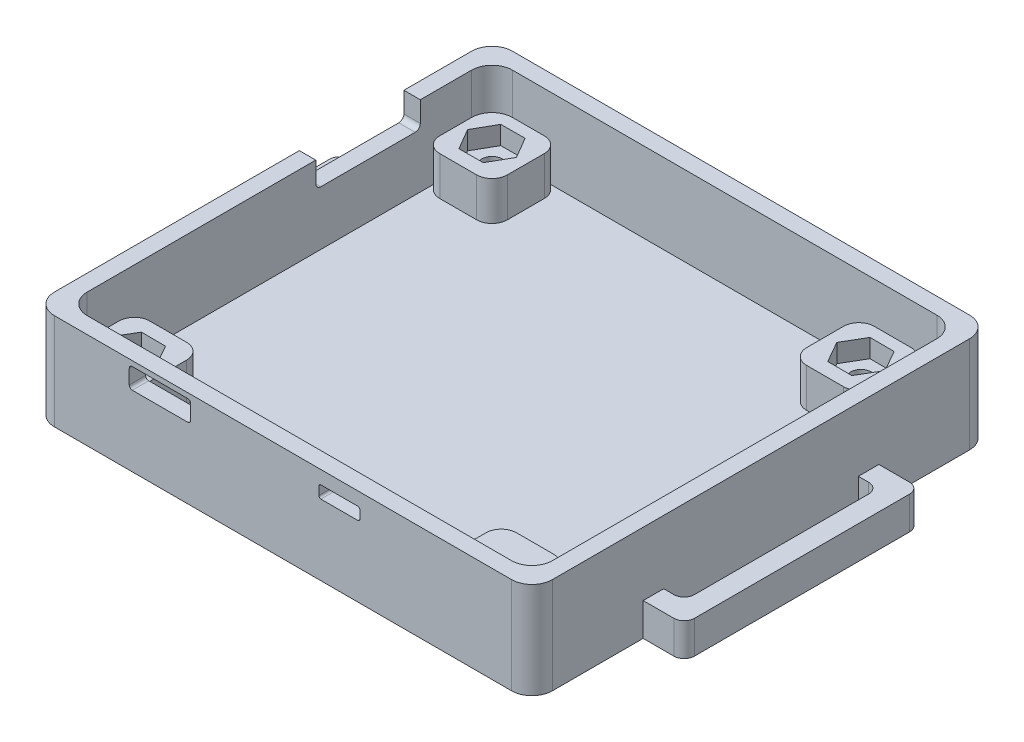
SolidWorks part; units mm, degrees
ref_plane "前视基准面" through (0, 0, 0) normal (0, 0, 1) x (1, 0, 0)
ref_plane "上视基准面" through (0, 0, 0) normal (0, 1, 0) x (1, 0, 0)
ref_plane "右视基准面" through (0, 0, 0) normal (1, 0, 0) x (0, 0, -1)
other "Configuration Table"
sketch "草图1" plane through (0, 0, 0) normal (0, 1, 0) x (1, 0, 0)
  line L0 (-22.3, 20.35) -> (22.3, -20.35) construction
  line L1 (-22.3, -22.35) -> (22.3, -22.35)
  line L2 (-24.3, -20.35) -> (-24.3, 20.35)
  line L3 (-22.3, 22.35) -> (22.3, 22.35)
  line L4 (24.3, -20.35) -> (24.3, 20.35)
  line L5 (0, 22.35) -> (0, -22.35) construction
  line L6 (-14.7715, 0) -> (34.2942, 0) construction
  line L7 (22.3, 20.35) -> (-22.3, -20.35) construction
  arc A0 (-22.3, -22.35) -> (-24.3, -20.35) centre (-22.3, -20.35) cw
  arc A1 (22.3, -22.35) -> (24.3, -20.35) centre (22.3, -20.35) ccw
  arc A2 (22.3, 22.35) -> (24.3, 20.35) centre (22.3, 20.35) cw
  arc A3 (-24.3, 20.35) -> (-22.3, 22.35) centre (-22.3, 20.35) cw
  point P0 (0, 0)
  point P6 (-24.3, -22.35)
  point P9 (24.3, -22.35)
  point P15 (-24.3, 22.35)
  point P16 (0, 0)
  point P17 (0, 0)
  dimension "D3" = 2
  dimension "D1" = 44.7
  dimension "D2" = 48.6
extrude "凸台-拉伸1" add sketch "草图1" along normal blind 9.4
sketch "草图2" plane through (0, 9.4, 0) normal (0, 1, 0) x (1, 0, 0)
  line L1 (-20.7, -20.75) -> (20.7, -20.75)
  line L2 (-22.7, -18.75) -> (-22.7, 18.75)
  line L3 (-20.7, 20.75) -> (20.7, 20.75)
  line L4 (22.7, -18.75) -> (22.7, 18.75)
  line L5 (0, 20.75) -> (0, -20.75) construction
  line L6 (-22.7, 0) -> (22.7, 0) construction
  arc A0 (20.7, -20.75) -> (22.7, -18.75) centre (20.7, -18.75) ccw
  arc A1 (-20.7, -20.75) -> (-22.7, -18.75) centre (-20.7, -18.75) cw
  arc A2 (20.7, 20.75) -> (22.7, 18.75) centre (20.7, 18.75) cw
  arc A3 (-22.7, 18.75) -> (-20.7, 20.75) centre (-20.7, 18.75) cw
  point P0 (0, 0)
  point P9 (-22.7, -20.75)
  point P12 (22.7, 20.75)
  point P15 (-22.7, 20.75)
  dimension "D3" = 2
  dimension "D1" = 41.5
  dimension "D2" = 45.4
extrude "切除-拉伸1" cut sketch "草图2" against normal blind 7.8
sketch "草图3" plane through (0, 1.6, 0) normal (0, 1, 0) x (1, 0, 0)
  line L0 (-22.7, 18.75) -> (-22.7, -18.75) construction
  line L1 (-21.2, -14.15) -> (-17.6, -14.15)
  line L2 (-22.7, -15.65) -> (-22.7, -20.75)
  line L3 (-22.7, -20.75) -> (-17.6, -20.75)
  line L4 (-16.1, -15.65) -> (-16.1, -19.25)
  line L8 (-20.7, -20.75) -> (20.7, -20.75) construction
  line L9 (-20.7, -20.75) -> (20.7, -20.75) construction
  line L10 (0, 0) -> (-37.0152, 0) construction
  line L11 (-22.7, 20.75) -> (-17.6, 20.75)
  line L12 (-16.1, 15.65) -> (-16.1, 19.25)
  line L13 (-21.2, 14.15) -> (-17.6, 14.15)
  line L14 (-22.7, 15.65) -> (-22.7, 20.75)
  line L15 (-1.5, 15.7499) -> (-1.5, -23.3817) construction
  line L16 (19.7, 15.65) -> (19.7, 19.25)
  line L17 (18.2, 20.75) -> (14.6, 20.75)
  line L18 (13.1, 15.65) -> (13.1, 19.25)
  line L19 (18.2, 14.15) -> (14.6, 14.15)
  line L20 (18.2, -14.15) -> (14.6, -14.15)
  line L21 (13.1, -15.65) -> (13.1, -19.25)
  line L22 (18.2, -20.75) -> (14.6, -20.75)
  line L23 (19.7, -15.65) -> (19.7, -19.25)
  arc A0 (-17.6, -20.75) -> (-16.1, -19.25) centre (-17.6, -19.25) ccw
  arc A1 (-21.2, -14.15) -> (-22.7, -15.65) centre (-21.2, -15.65) ccw
  arc A2 (-17.6, -14.15) -> (-16.1, -15.65) centre (-17.6, -15.65) cw
  arc A3 (-17.6, 20.75) -> (-16.1, 19.25) centre (-17.6, 19.25) cw
  arc A4 (-17.6, 14.15) -> (-16.1, 15.65) centre (-17.6, 15.65) ccw
  arc A5 (-21.2, 14.15) -> (-22.7, 15.65) centre (-21.2, 15.65) cw
  arc A6 (18.2, 14.15) -> (19.7, 15.65) centre (18.2, 15.65) ccw
  arc A7 (14.6, 20.75) -> (13.1, 19.25) centre (14.6, 19.25) ccw
  arc A8 (14.6, 14.15) -> (13.1, 15.65) centre (14.6, 15.65) cw
  arc A9 (19.7, 19.25) -> (18.2, 20.75) centre (18.2, 19.25) ccw
  arc A10 (18.2, -14.15) -> (19.7, -15.65) centre (18.2, -15.65) cw
  arc A11 (14.6, -14.15) -> (13.1, -15.65) centre (14.6, -15.65) ccw
  arc A12 (14.6, -20.75) -> (13.1, -19.25) centre (14.6, -19.25) cw
  arc A13 (19.7, -19.25) -> (18.2, -20.75) centre (18.2, -19.25) cw
  point P13 (-16.1, -20.75)
  point P16 (-22.7, -14.15)
  point P19 (-16.1, -14.15)
  point P47 (19.7, 20.75)
  dimension "D3" = 1.5
  dimension "D5" = 1.5
  dimension "D1" = 6.6
  dimension "D2" = 6.6
  dimension "D4" = 21.2
extrude "凸台-拉伸2" add sketch "草图3" along normal blind 3.8
sketch "草图4" plane through (0, 5.4, 0) normal (0, 1, 0) x (1, 0, 0)
  line L0 (-22.7, 18.75) -> (-22.7, -18.75) construction
  line L1 (-18.329, -19.6072) -> (-17.1329, -17.5645)
  line L2 (-17.1329, -17.5645) -> (-18.3039, -15.5073)
  line L3 (-18.3039, -15.5073) -> (-20.671, -15.4928)
  line L4 (-20.671, -15.4928) -> (-21.8671, -17.5355)
  line L5 (-21.8671, -17.5355) -> (-20.6961, -19.5927)
  line L6 (-20.6961, -19.5927) -> (-18.329, -19.6072)
  line L8 (-20.7, -20.75) -> (20.7, -20.75) construction
  line L9 (0, 0) -> (-33.3871, 0) construction
  line L10 (-20.6961, 19.5927) -> (-18.329, 19.6072)
  line L11 (-21.8671, 17.5355) -> (-20.6961, 19.5927)
  line L12 (-20.671, 15.4928) -> (-21.8671, 17.5355)
  line L13 (-18.3039, 15.5073) -> (-20.671, 15.4928)
  line L14 (-17.1329, 17.5645) -> (-18.3039, 15.5073)
  line L15 (-18.329, 19.6072) -> (-17.1329, 17.5645)
  line L16 (-1.5, 15.3612) -> (-1.5, -12.6702) construction
  line L17 (18.8671, 17.5355) -> (17.6961, 19.5927)
  line L18 (17.671, 15.4928) -> (18.8671, 17.5355)
  line L19 (15.3039, 15.5073) -> (17.671, 15.4928)
  line L20 (14.1329, 17.5645) -> (15.3039, 15.5073)
  line L21 (15.329, 19.6072) -> (14.1329, 17.5645)
  line L22 (17.6961, 19.5927) -> (15.329, 19.6072)
  circle A0 centre (-19.5, -17.55) radius 2.05 construction
  dimension "D1" = 4.1
  dimension "D2" = 3.2
  dimension "D3" = 3.2
  dimension "D4" = 21.2
sketch "草图5" plane through (0, 5.4, 0) normal (0, 1, 0) x (1, 0, 0)
  line L0 (-22.7, 18.75) -> (-22.7, -18.75) construction
  line L2 (-20.7, -20.75) -> (20.7, -20.75) construction
  line L3 (0, 0) -> (-40.1682, 0) construction
  line L4 (-1.5, 11.1284) -> (-1.5, -10.2514) construction
  circle A0 centre (-19.5, -17.55) radius 1
  circle A3 centre (-19.5, 17.55) radius 1
  circle A4 centre (16.5, 17.55) radius 1
  dimension "D1" = 3.2
  dimension "D2" = 3.2
  dimension "D3" = 21.2
extrude "切除-拉伸2" cut sketch "草图4" against normal blind 1.8
extrude "切除-拉伸4" cut sketch "草图5" against normal blind 3.8
sketch "草图6" plane through (-24.3, 0, 0) normal (-1, 0, 0) x (0, 0, 1)
  line L1 (-13.25, 6.9) -> (-4.05, 6.9)
  line L2 (-13.75, 7.4) -> (-13.75, 10.4)
  line L3 (-13.75, 10.4) -> (-3.55, 10.4)
  line L4 (-3.55, 7.4) -> (-3.55, 10.4)
  line L5 (-8.65, 10.4) -> (-8.65, 6.9) construction
  line L6 (-13.75, 8.9) -> (-3.55, 8.9) construction
  line L9 (20.75, 5.4) -> (20.75, 9.4) construction
  line L11 (-15.65, 1.6) -> (15.65, 1.6) construction
  arc A0 (-4.05, 6.9) -> (-3.55, 7.4) centre (-4.05, 7.4) ccw
  arc A1 (-13.25, 6.9) -> (-13.75, 7.4) centre (-13.25, 7.4) cw
  point P0 (-8.65, 8.9)
  dimension "D5" = 0.5
  dimension "D1" = 29.4
  dimension "D2" = 10.2
  dimension "D3" = 3.5
  dimension "D4" = 5.3
extrude "切除-拉伸5" cut sketch "草图6" against normal blind 2.8
sketch "草图7" plane through (0, 0, 22.35) normal (0, 0, 1) x (1, 0, 0)
  line L0 (-22.7, 5.4) -> (-22.7, 1.6) construction
  line L1 (-14.7, 8.9) -> (-9.3, 8.9)
  line L2 (-15, 8.6) -> (-15, 7.2)
  line L3 (-14.7, 6.9) -> (-9.3, 6.9)
  line L4 (-9, 8.6) -> (-9, 7.2)
  line L5 (-12, 6.9) -> (-12, 8.9) construction
  line L6 (-15, 7.9) -> (-9, 7.9) construction
  line L7 (-17.6, 1.6) -> (14.6, 1.6) construction
  arc A0 (-15, 7.2) -> (-14.7, 6.9) centre (-14.7, 7.2) ccw
  arc A1 (-9.3, 6.9) -> (-9, 7.2) centre (-9.3, 7.2) ccw
  arc A2 (-9.3, 8.9) -> (-9, 8.6) centre (-9.3, 8.6) cw
  arc A3 (-14.7, 8.9) -> (-15, 8.6) centre (-14.7, 8.6) ccw
  point P0 (-12, 7.9)
  point P10 (-15, 6.9)
  point P13 (-9, 6.9)
  point P16 (-9, 8.9)
  dimension "D5" = 0.3
  dimension "D1" = 10.7
  dimension "D2" = 6
  dimension "D3" = 2
  dimension "D4" = 5.3
extrude "切除-拉伸6" cut sketch "草图7" against normal blind 2.8
sketch "草图8" plane through (0, 0, 22.35) normal (0, 0, 1) x (1, 0, 0)
  line L0 (-22.7, 5.4) -> (-22.7, 1.6) construction
  line L1 (3.7, 8.1) -> (7.3, 8.1)
  line L2 (3.5, 7.9) -> (3.5, 7.1)
  line L3 (3.7, 6.9) -> (7.3, 6.9)
  line L4 (7.5, 7.9) -> (7.5, 7.1)
  line L5 (5.5, 6.9) -> (5.5, 8.1) construction
  line L6 (3.5, 7.5) -> (7.5, 7.5) construction
  line L7 (-17.6, 1.6) -> (14.6, 1.6) construction
  arc A0 (3.5, 7.1) -> (3.7, 6.9) centre (3.7, 7.1) ccw
  arc A1 (7.3, 6.9) -> (7.5, 7.1) centre (7.3, 7.1) ccw
  arc A2 (7.3, 8.1) -> (7.5, 7.9) centre (7.3, 7.9) cw
  arc A3 (3.7, 8.1) -> (3.5, 7.9) centre (3.7, 7.9) ccw
  point P0 (5.5, 7.5)
  point P10 (3.5, 6.9)
  point P13 (7.5, 6.9)
  point P19 (3.5, 8.1)
  dimension "D5" = 0.2
  dimension "D1" = 28.2
  dimension "D2" = 5.3
  dimension "D3" = 4
  dimension "D4" = 1.2
extrude "切除-拉伸7" cut sketch "草图8" against normal blind 2.8
sketch "草图12" plane through (0, 1.6, 0) normal (0, 1, 0) x (1, 0, 0)
  line L0 (-24.3, 20.35) -> (-24.3, -20.35) construction
  line L1 (-27.3, 11.5) -> (-24.3, 11.5)
  line L2 (-28.3, 10.5) -> (-28.3, -10.5)
  line L3 (-27.3, -11.5) -> (-24.3, -11.5)
  line L4 (-24.3, 11.5) -> (-24.3, -11.5)
  line L5 (-25.8, -11.5) -> (-25.8, 11.5) construction
  line L6 (-28.3, 0) -> (-24.3, 0) construction
  line L7 (0, 24.1491) -> (0, -25.1278) construction
  line L8 (22.3, 22.35) -> (-22.3, 22.35) construction
  line L9 (27.3, -11.5) -> (24.3, -11.5)
  line L10 (24.3, 11.5) -> (24.3, -11.5)
  line L11 (27.3, 11.5) -> (24.3, 11.5)
  line L12 (28.3, 10.5) -> (28.3, -10.5)
  arc A0 (-28.3, -10.5) -> (-27.3, -11.5) centre (-27.3, -10.5) ccw
  arc A1 (-27.3, 11.5) -> (-28.3, 10.5) centre (-27.3, 10.5) ccw
  arc A2 (28.3, -10.5) -> (27.3, -11.5) centre (27.3, -10.5) cw
  arc A3 (27.3, 11.5) -> (28.3, 10.5) centre (27.3, 10.5) cw
  point P0 (-25.8, 0)
  dimension "D3" = 1
  dimension "D1" = 24.3
  dimension "D2" = 22.35
  dimension "D4" = 4
  dimension "D5" = 23
extrude "凸台-拉伸3" add sketch "草图12" along normal mid plane 3.2
sketch "草图13" plane through (0, 3.2, 0) normal (0, 1, 0) x (1, 0, 0)
  line L0 (-24.3, 13.25) -> (-24.3, 4.05) construction
  line L1 (-25.3, 9.5) -> (-24.3, 9.5)
  line L2 (-26.3, 8.5) -> (-26.3, -8.5)
  line L3 (-25.3, -9.5) -> (-24.3, -9.5)
  line L4 (-24.3, 9.5) -> (-24.3, -9.5)
  line L5 (-28.3, 10.5) -> (-28.3, -10.5) construction
  line L6 (-26.3, 0) -> (-24.3, 0) construction
  line L7 (0, 0) -> (0, 24.5271) construction
  line L8 (25.3, -9.5) -> (24.3, -9.5)
  line L9 (24.3, 9.5) -> (24.3, -9.5)
  line L10 (0, 0) -> (-58.6575, 0) construction
  line L11 (25.3, 9.5) -> (24.3, 9.5)
  line L12 (-27.3, -11.5) -> (-24.3, -11.5) construction
  line L13 (26.3, 8.5) -> (26.3, -8.5)
  arc A0 (-26.3, -8.5) -> (-25.3, -9.5) centre (-25.3, -8.5) ccw
  arc A1 (-25.3, 9.5) -> (-26.3, 8.5) centre (-25.3, 8.5) ccw
  arc A2 (26.3, -8.5) -> (25.3, -9.5) centre (25.3, -8.5) cw
  arc A3 (25.3, 9.5) -> (26.3, 8.5) centre (25.3, 8.5) cw
  point P0 (-27.8, 0.5)
  dimension "D5" = 1
  dimension "D1" = 19
  dimension "D2" = 2
  dimension "D3" = 2
  dimension "D4" = 24.3
extrude "切除-拉伸8" cut sketch "草图13" against normal blind 3.2
